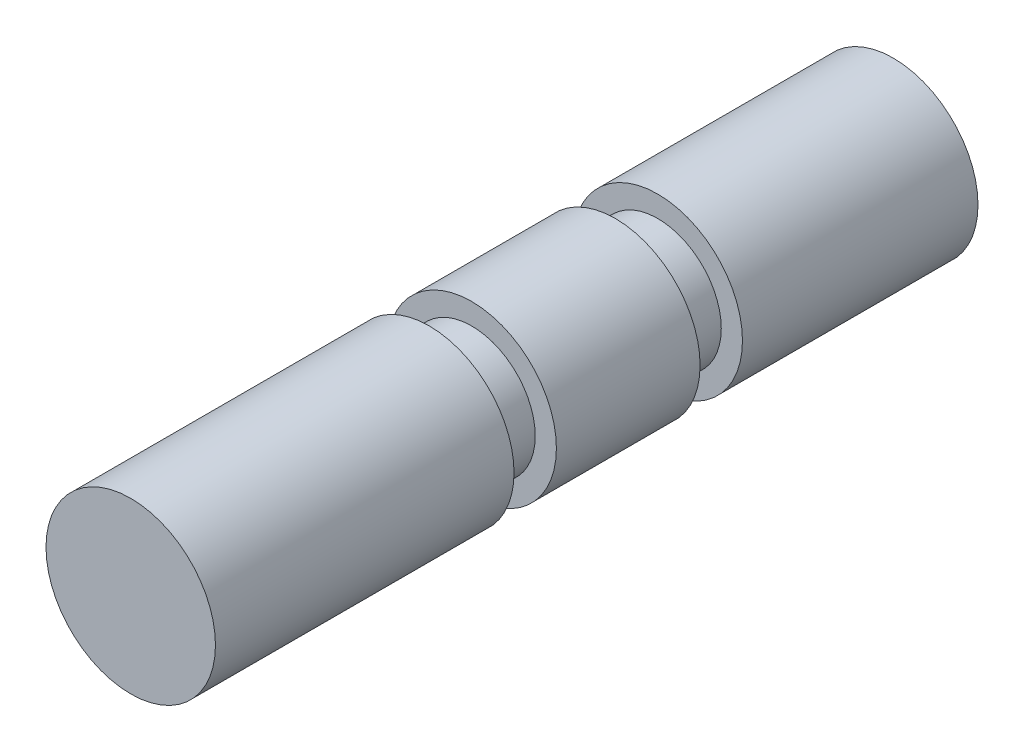
SolidWorks part; units mm, degrees
ref_plane "Front Plane" through (0, 0, 0) normal (0, 0, 1) x (1, 0, 0)
ref_plane "Top Plane" through (0, 0, 0) normal (0, 1, 0) x (1, 0, 0)
ref_plane "Right Plane" through (0, 0, 0) normal (1, 0, 0) x (0, 0, -1)
sketch "Sketch2" plane through (0, 0, 0) normal (1, 0, 0) x (0, 0, -1)
  line L0 (0, 0) -> (0, 50)
  line L1 (0, 50) -> (426.2, 50)
  line L2 (0, 0) -> (700, 0)
  line L3 (700, 0) -> (700, 50)
  line L4 (561, 50) -> (561, 37.5)
  line L5 (561, 37.5) -> (536, 37.5)
  line L6 (536, 37.5) -> (536, 50)
  line L7 (451.2, 50) -> (451.2, 37.5)
  line L8 (451.2, 37.5) -> (426.2, 37.5)
  line L9 (426.2, 37.5) -> (426.2, 50)
  line L10 (561, 50) -> (700, 50)
  line L11 (451.2, 50) -> (536, 50)
  dimension "D1" = 50
  dimension "D2" = 700
  dimension "D3" = 139
  dimension "D4" = 12.5
  dimension "D5" = 25
  dimension "D6" = 248.8
  dimension "D7" = 25
revolve "Revolve1" add sketch "Sketch2" angle 360 about L2
sketch "Sketch3" plane through (0, 0, 0) normal (0, 0, 1) x (1, 0, 0)
  circle A0 centre (0, 0) radius 50
extrude "Cut-Extrude1" cut sketch "Sketch3" against normal blind 250
